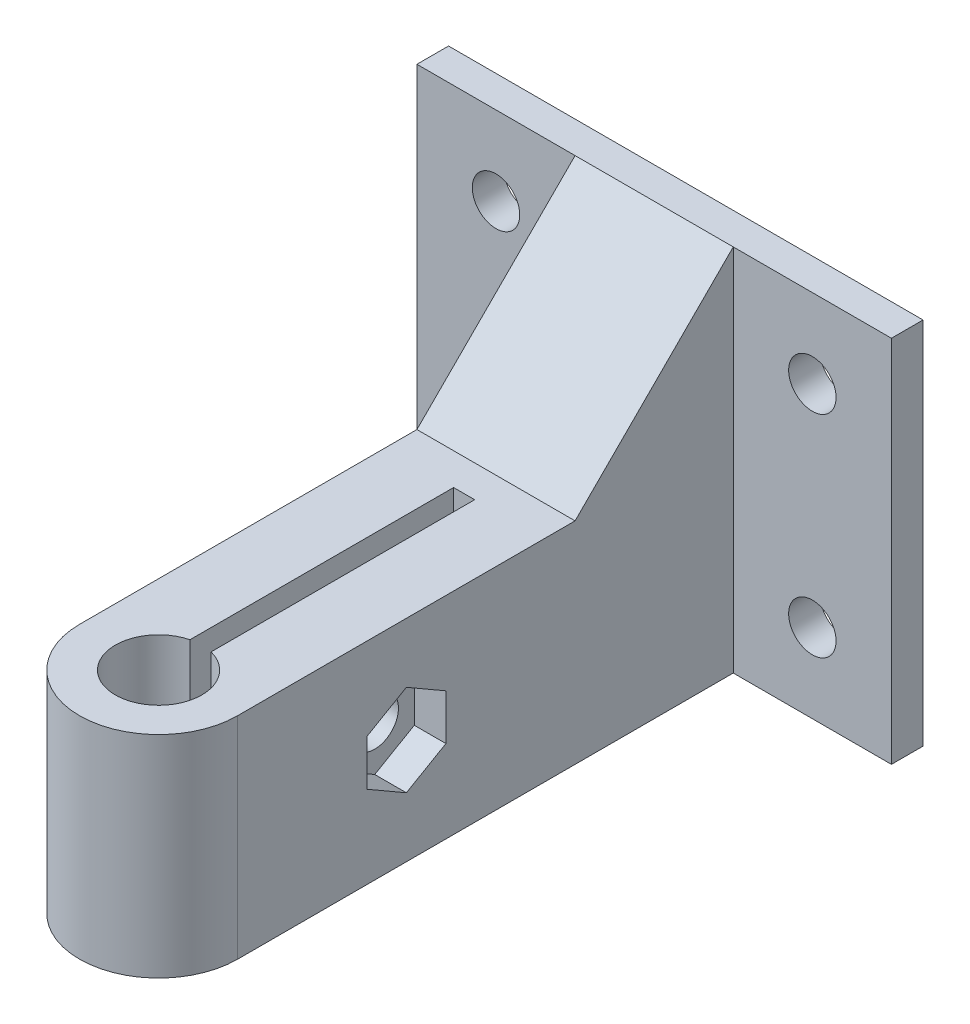
SolidWorks part; units mm, degrees
ref_plane "Front Plane" through (0, 0, 0) normal (0, 0, 1) x (1, 0, 0)
ref_plane "Top Plane" through (0, 0, 0) normal (0, 1, 0) x (1, 0, 0)
ref_plane "Right Plane" through (0, 0, 0) normal (1, 0, 0) x (0, 0, -1)
sketch "Sketch1" plane through (0, 0, 0) normal (0, 0, 1) x (1, 0, 0)
  line L0 (-15, 5) -> (-15, -15) construction
  line L1 (-22.5, -22.5) -> (22.5, -22.5)
  line L2 (-22.5, -22.5) -> (-22.5, 22.5)
  line L3 (-22.5, 22.5) -> (22.5, 22.5)
  line L4 (22.5, -22.5) -> (22.5, 22.5)
  line L7 (15, 5) -> (-15, 5) construction
  line L8 (-15, -15) -> (15, -15) construction
  circle A0 centre (-15, 5) radius 2.25
  circle A1 centre (15, 5) radius 2.25
  circle A2 centre (15, -15) radius 2.25
  circle A3 centre (-15, -15) radius 2.25
  point P0 (0, 0)
  dimension "D2" = 4.5
  dimension "D1" = 45
  dimension "D3" = 30
  dimension "D4" = 30
  dimension "D5" = 20
extrude "Boss-Extrude1" add sketch "Sketch1" along normal blind 3
sketch "Sketch3" plane through (0, -22.5, 0) normal (0, -1, 0) x (-1, 0, 0)
  line L0 (22.5, -3) -> (-22.5, -3) construction
  line L1 (7.5, -3) -> (-7.5, -3)
  line L2 (7.5, -3) -> (7.5, -50)
  line L3 (1, -46.0238) -> (1, -21.0238)
  line L4 (-7.5, -3) -> (-7.5, -50)
  line L6 (22.5, 0) -> (-22.5, 0) construction
  line L7 (1, -21.0238) -> (-1, -21.0238)
  line L8 (-1, -21.0238) -> (-1, -46.0238)
  line L9 (7.5, -50) -> (0, -50) construction
  arc A0 (-1, -46.0238) -> (1, -46.0238) centre (0, -50) ccw
  arc A1 (7.5, -50) -> (-7.5, -50) centre (0, -50) cw
  point P6 (0, -3)
  point P9 (0, 0)
  point P14 (0, -21.0238)
  dimension "D3" = 8.2
  dimension "D1" = 0
  dimension "D2" = 47
  dimension "D4" = 15
  dimension "D5" = 0
  dimension "D6" = 2
  dimension "D7" = 25
extrude "Boss-Extrude2" add sketch "Sketch3" against normal blind 20
chamfer "Chamfer1" distance 15 angle 45 1 edges at (0, -2.5, 3)
sketch "Sketch4" plane through (-7.5, 0, 0) normal (-1, 0, 0) x (0, 0, 1)
  line L0 (34, -2.5) -> (34, -22.5) construction
  line L1 (50, -2.5) -> (18, -2.5) construction
  line L2 (50, -22.5) -> (3, -22.5) construction
  circle A0 centre (34, -12.5) radius 2.25
  dimension "D1" = 4.5
extrude "Cut-Extrude1" cut sketch "Sketch4" against normal blind 20
sketch "Sketch5" plane through (7.5, 0, 0) normal (1, 0, 0) x (0, 0, -1)
  line L1 (-34, -16.8301) -> (-30.25, -14.6651)
  line L2 (-30.25, -14.6651) -> (-30.25, -10.3349)
  line L3 (-30.25, -10.3349) -> (-34, -8.1699)
  line L4 (-34, -8.1699) -> (-37.75, -10.3349)
  line L5 (-37.75, -10.3349) -> (-37.75, -14.6651)
  line L6 (-37.75, -14.6651) -> (-34, -16.8301)
  circle A0 centre (-34, -12.5) radius 3.75 construction
  dimension "D1" = 7.5
extrude "Cut-Extrude2" cut sketch "Sketch5" against normal blind 3
sketch "Sketch6" plane through (0, 0, 3) normal (0, 0, 1) x (1, 0, 0)
  line L0 (-22.5, 22.5) -> (-22.5, -22.5) construction
  line L1 (22.5, 22.5) -> (-22.5, 22.5)
  line L2 (22.5, 22.5) -> (22.5, 12.5)
  line L3 (22.5, 12.5) -> (-22.5, 12.5)
  line L4 (-22.5, 22.5) -> (-22.5, 12.5)
extrude "Cut-Extrude3" cut sketch "Sketch6" against normal blind 10
